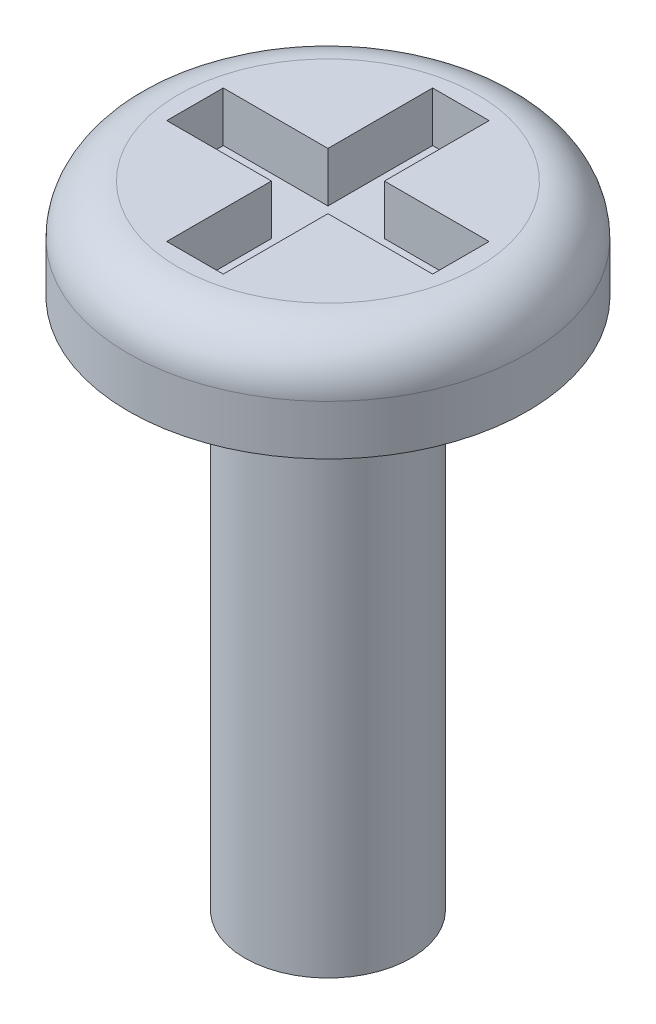
SolidWorks part; units mm, degrees
ref_plane "Front Plane" through (0, 0, 0) normal (0, 0, 1) x (1, 0, 0)
ref_plane "Top Plane" through (0, 0, 0) normal (0, 1, 0) x (1, 0, 0)
ref_plane "Right Plane" through (0, 0, 0) normal (1, 0, 0) x (0, 0, -1)
sketch "Sketch3" plane through (0, 0, 0) normal (0, 1, 0) x (1, 0, 0)
  circle A0 centre (0, 0) radius 1.25
  dimension "D1" = 2.5
extrude "Boss-Extrude1" add sketch "Sketch3" along normal blind 8
sketch "Sketch4" plane through (0, 8, 0) normal (0, 1, 0) x (1, 0, 0)
  circle A0 centre (0, 0) radius 3
  dimension "D1" = 6
extrude "Boss-Extrude2" add sketch "Sketch4" along normal blind 1.5
fillet "Fillet3" radius 0.75 1 edges at (0, 9.5, 3)
sketch "Sketch6" plane through (0, 9.5, 0) normal (0, 1, 0) x (1, 0, 0)
  line L0 (0.425, 0.425) -> (2, 0.425)
  line L1 (-2, 0.425) -> (-0.425, 0.425)
  line L2 (-2, 0.425) -> (-2, -0.425)
  line L3 (-2, -0.425) -> (-0.425, -0.425)
  line L4 (2, 0.425) -> (2, -0.425)
  line L5 (0, 0) -> (0.425, -0.0903) construction
  line L7 (-0.425, 2) -> (0.425, 2)
  line L8 (-0.425, 2) -> (-0.425, 0.425)
  line L9 (-0.425, -2) -> (0.425, -2)
  line L10 (0.425, 2) -> (0.425, 0.425)
  line L14 (-0.425, -0.425) -> (-0.425, -2)
  line L17 (0.425, -0.425) -> (0.425, -2)
  line L19 (0.425, -0.425) -> (2, -0.425)
  point P0 (0, 0)
  point P6 (0, 0)
  dimension "D1" = 4
  dimension "D2" = 4
  dimension "D3" = 0.85
  dimension "D4" = 0.85
extrude "Cut-Extrude4" cut sketch "Sketch6" against normal blind 0.75
sketch "Sketch7" plane through (0, 0, 0) normal (0, 0, 1) x (1, 0, 0)
  line L0 (-7.4335, 7) -> (10.8456, 7)
  dimension "D1" = 7
split line "Split Line1"
